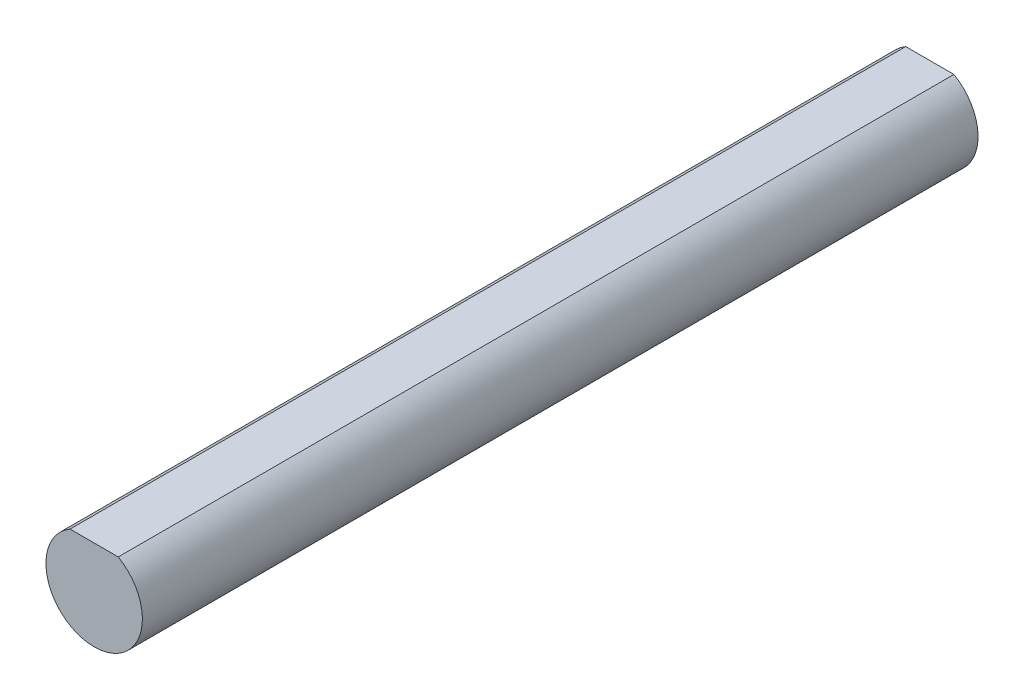
SolidWorks part; units mm, degrees
ref_plane "Front Plane" through (0, 0, 0) normal (0, 0, 1) x (1, 0, 0)
ref_plane "Top Plane" through (0, 0, 0) normal (0, 1, 0) x (1, 0, 0)
ref_plane "Right Plane" through (0, 0, 0) normal (1, 0, 0) x (0, 0, -1)
sketch "Sketch2" plane through (0, 0, 0) normal (0, 0, 1) x (1, 0, 0)
  line L0 (-1.5, 2.5981) -> (1.5, 2.5981)
  arc A0 (-1.5, 2.5981) -> (1.5, 2.5981) centre (0, 0) ccw
  dimension "D1" = 6
  dimension "D2" = 3
extrude "Boss-Extrude1" add sketch "Sketch2" along normal blind 52
